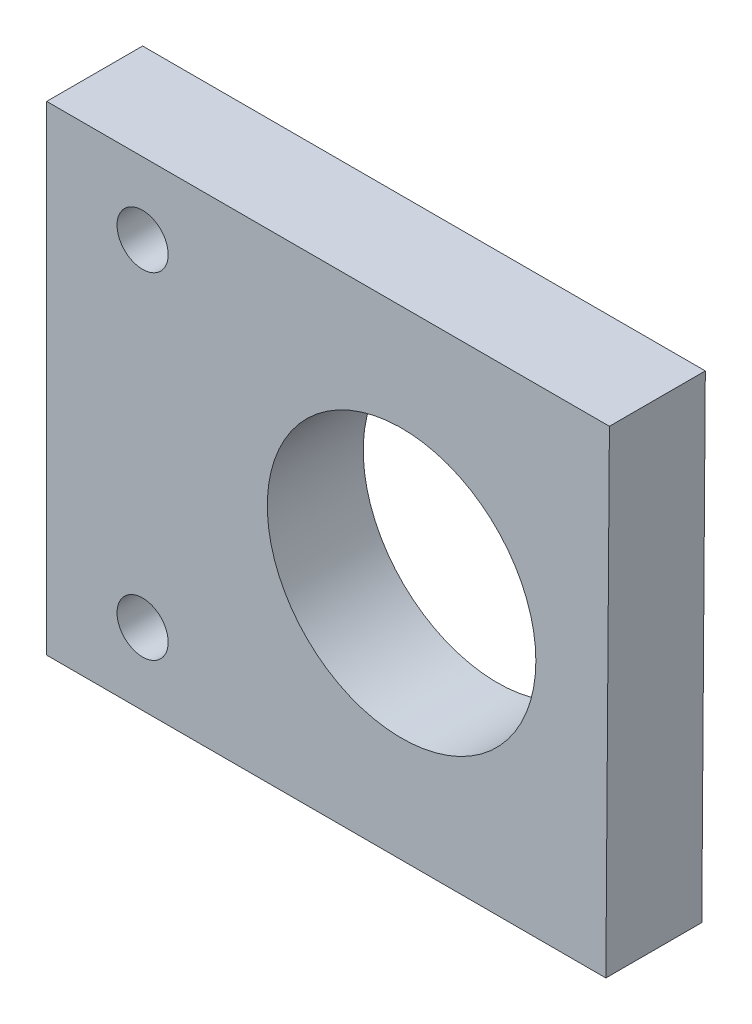
SolidWorks part; units mm, degrees
ref_plane "前视基准面" through (0, 0, 0) normal (0, 0, 1) x (1, 0, 0)
ref_plane "上视基准面" through (0, 0, 0) normal (0, 1, 0) x (1, 0, 0)
ref_plane "右视基准面" through (0, 0, 0) normal (1, 0, 0) x (0, 0, -1)
sketch "草图1" plane through (0, 0, 0) normal (0, 0, 1) x (1, 0, 0)
  line L0 (-28.0746, 0) -> (60.6911, 0) construction
  line L1 (-19, 37.5) -> (11, 37.5)
  line L2 (-19, -37.5) -> (19, -37.5)
  line L3 (-19, -37.5) -> (-19, 37.5)
  line L4 (-19, 37.5) -> (19, 37.5)
  line L6 (-19, -37.5) -> (19, 37.5) construction
  line L7 (-19, 37.5) -> (19, -37.5) construction
  line L8 (-19, 0) -> (-19, 26.25)
  line L9 (19, 37.5) -> (69, 37.5)
  line L10 (69, 37.5) -> (68.4464, -37.5)
  line L11 (68.4464, -37.5) -> (19, -37.5)
  circle A2 centre (-4, 26.25) radius 4
  circle A3 centre (-4, -26.25) radius 4
  circle A4 centre (36.5, 0) radius 21
  point P2 (0, 0)
extrude "凸台-拉伸1" add sketch "草图1" along normal blind 15
